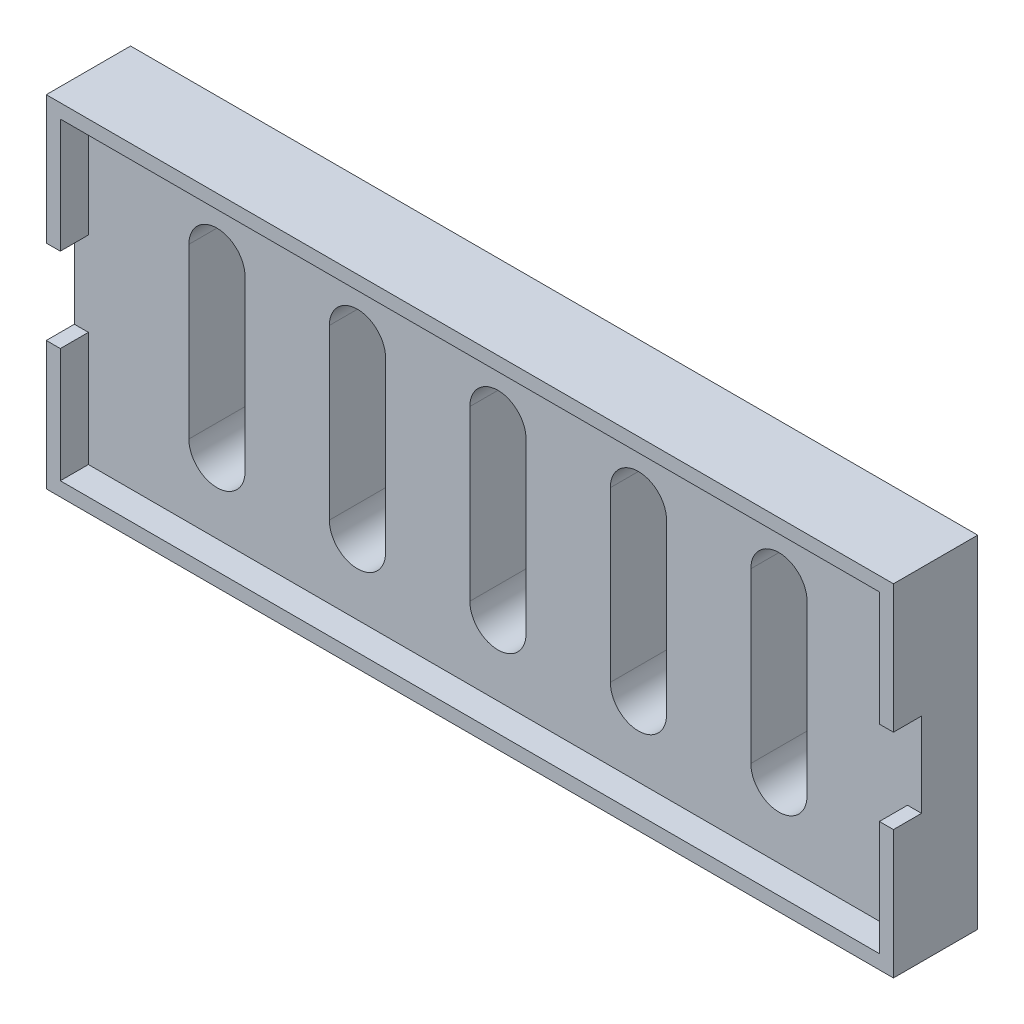
SolidWorks part; units mm, degrees
ref_plane "Front" through (0, 0, 0) normal (0, 0, 1) x (1, 0, 0)
ref_plane "Top" through (0, 0, 0) normal (0, 1, 0) x (1, 0, 0)
ref_plane "Right" through (0, 0, 0) normal (1, 0, 0) x (0, 0, -1)
sketch "Sketch1" plane through (0, 0, 0) normal (0, 0, 1) x (1, 0, 0)
  line L0 (15.275, 6.275) -> (15.275, -6.275) construction
  line L5 (-15.275, 6.275) -> (15.275, -6.275) construction
  line L6 (-15.275, -6.275) -> (15.275, 6.275) construction
  line L7 (15.275, 6.275) -> (-15.275, 6.275) construction
  line L8 (-15.275, 6.275) -> (-15.275, -6.275) construction
  line L9 (15.275, -6.275) -> (-15.275, -6.275) construction
  line L14 (15.075, 6.075) -> (-15.075, 6.075)
  line L15 (-15.075, 6.075) -> (-15.075, -6.075)
  line L16 (15.075, -6.075) -> (-15.075, -6.075)
  line L17 (15.075, 6.075) -> (15.075, -6.075)
  point P0 (0, 0)
  dimension "D1" = 30.55
  dimension "D2" = 12.55
  dimension "D3" = 0.2
extrude "Boss-Extrude1" add sketch "Sketch1" along normal blind 2
sketch "Sketch2" plane through (0, 0, 2) normal (0, 0, 1) x (1, 0, 0)
  line L0 (15.075, 6.075) -> (-15.075, 6.075) construction
  line L1 (15.075, 6.075) -> (-15.075, 6.075)
  line L2 (-15.075, 6.075) -> (-15.075, -6.075) construction
  line L3 (-15.075, 6.075) -> (-15.075, -6.075)
  line L8 (14.575, -5.575) -> (14.575, 5.575)
  line L9 (14.575, 5.575) -> (-14.575, 5.575)
  line L10 (-14.575, 5.575) -> (-14.575, -5.575)
  line L11 (-14.575, -5.575) -> (14.575, -5.575)
  line L12 (14.575, -5.575) -> (14.575, 5.575)
  line L13 (14.575, 5.575) -> (-14.575, 5.575)
  line L14 (-14.575, 5.575) -> (-14.575, -5.575)
  line L15 (-14.575, -5.575) -> (14.575, -5.575)
  line L20 (-15.075, -6.075) -> (15.075, -6.075) construction
  line L21 (-15.075, -6.075) -> (15.075, -6.075)
  line L22 (15.075, -6.075) -> (15.075, 6.075) construction
  line L23 (15.075, -6.075) -> (15.075, 6.075)
  dimension "D1" = 0.5
extrude "Boss-Extrude2" add sketch "Sketch2" along normal blind 1
sketch "Sketch3" plane through (0, 0, 0) normal (0, 0, -1) x (-1, 0, 0)
  line L0 (-15.075, 0) -> (15.075, 0) construction
  line L2 (-1, -3) -> (-1, 3)
  line L4 (1, -3) -> (1, 3)
  line L5 (-1, -3) -> (1, 3) construction
  line L6 (-1, 3) -> (1, -3) construction
  line L7 (-15.075, -6.075) -> (-15.075, 6.075) construction
  line L8 (15.075, 6.075) -> (15.075, -6.075) construction
  line L9 (-6, -3) -> (-6, 3)
  line L10 (-4, -3) -> (-4, 3)
  line L11 (-11, -3) -> (-11, 3)
  line L12 (-9, -3) -> (-9, 3)
  line L13 (-1, -3) -> (-6, -3) construction
  line L14 (4, -3) -> (4, 3)
  line L15 (6, -3) -> (6, 3)
  line L16 (9, -3) -> (9, 3)
  line L17 (11, -3) -> (11, 3)
  line L18 (-1, -3) -> (4, -3) construction
  arc A0 (-1, 3) -> (1, 3) centre (0, 3) cw
  arc A1 (-1, -3) -> (1, -3) centre (0, -3) ccw
  arc A2 (-6, 3) -> (-4, 3) centre (-5, 3) cw
  arc A3 (-6, -3) -> (-4, -3) centre (-5, -3) ccw
  arc A4 (-11, 3) -> (-9, 3) centre (-10, 3) cw
  arc A5 (-11, -3) -> (-9, -3) centre (-10, -3) ccw
  arc A6 (4, 3) -> (6, 3) centre (5, 3) cw
  arc A7 (4, -3) -> (6, -3) centre (5, -3) ccw
  arc A8 (9, 3) -> (11, 3) centre (10, 3) cw
  arc A9 (9, -3) -> (11, -3) centre (10, -3) ccw
  point P0 (0, 0)
  dimension "D1" = 2
  dimension "D2" = 6
  dimension "D4" = 5
  dimension "D6" = 5
  dimension "D3" = 3
  dimension "D5" = 3
extrude "Cut-Extrude1" cut sketch "Sketch3" against normal up to surface (2 mm away) up to face at (0, 0, 2)
sketch "Sketch4" plane through (0, 0, 3) normal (0, 0, 1) x (1, 0, 0)
  line L0 (0, 6.075) -> (0, -6.075) construction
  line L3 (15.075, 6.075) -> (-15.075, 6.075) construction
  line L6 (-14.575, 5.575) -> (-14.575, -5.575) construction
  line L7 (-15.075, -1.5) -> (-14.575, -1.5)
  line L8 (-15.075, -1.5) -> (-15.075, 1.5)
  line L9 (-15.075, 1.5) -> (-14.575, 1.5)
  line L10 (-14.575, -1.5) -> (-14.575, 1.5)
  line L15 (-15.075, -6.075) -> (15.075, -6.075) construction
  line L16 (-15.075, 0) -> (15.075, 0) construction
  line L17 (-15.075, 6.075) -> (-15.075, -6.075) construction
  line L18 (15.075, -6.075) -> (15.075, 6.075) construction
  line L19 (15.075, 1.5) -> (14.575, 1.5)
  line L20 (14.575, -1.5) -> (14.575, 1.5)
  line L21 (15.075, -1.5) -> (14.575, -1.5)
  line L22 (15.075, -1.5) -> (15.075, 1.5)
  point P16 (-15.075, 0)
  dimension "D1" = 3
extrude "Cut-Extrude2" cut sketch "Sketch4" against normal up to surface (1 mm away) up to face at (-10, 0, 2)
